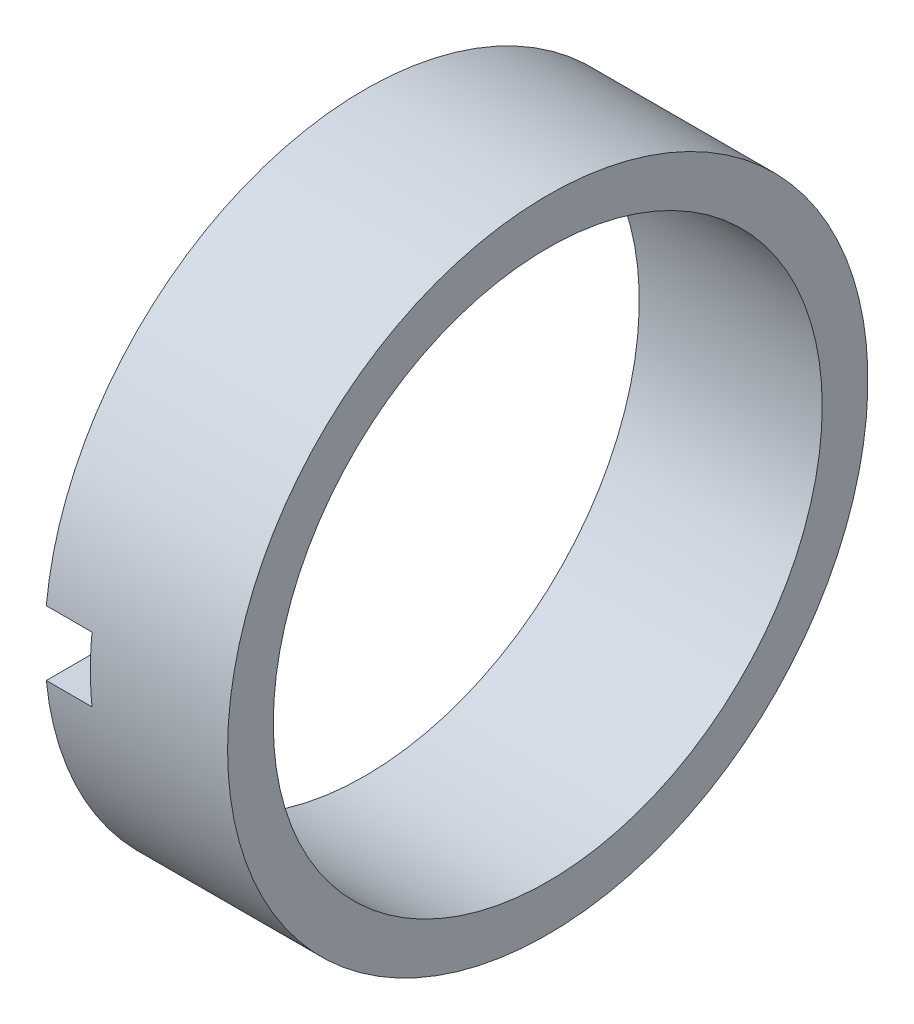
SolidWorks part; units mm, degrees
ref_plane "Front Plane" through (0, 0, 0) normal (1, 0, 0) x (0, 1, 0)
ref_plane "Top Plane" through (0, 0, 0) normal (0, 0, 1) x (0, 1, 0)
ref_plane "Right Plane" through (0, 0, 0) normal (0, 1, 0) x (-1, 0, 0)
sketch "Sketch1" plane through (0, 0, 0) normal (0, 0, 1) x (0, 1, 0)
  line L0 (133.35, 0) -> (133.35, -76.2)
  line L1 (133.35, -76.2) -> (114.3254, -76.2)
  line L2 (114.3254, -76.2) -> (114.3254, 0)
  line L3 (114.3254, 0) -> (133.35, 0)
  line L4 (0, 25.4) -> (0, -101.6) construction
revolve "Revolve1" add sketch "Sketch1" angle 360 about L4
sketch "Sketch2" plane through (0, 0, 0) normal (1, 0, 0) x (0, 1, 0)
  line L1 (-13.4874, 0) -> (13.4874, 0)
  line L2 (-13.4874, 0) -> (-13.4874, 266.7)
  line L3 (-13.4874, 266.7) -> (13.4874, 266.7)
  line L4 (13.4874, 0) -> (13.4874, 266.7)
extrude "Cut-Extrude2" cut sketch "Sketch2" along normal blind 19.05
